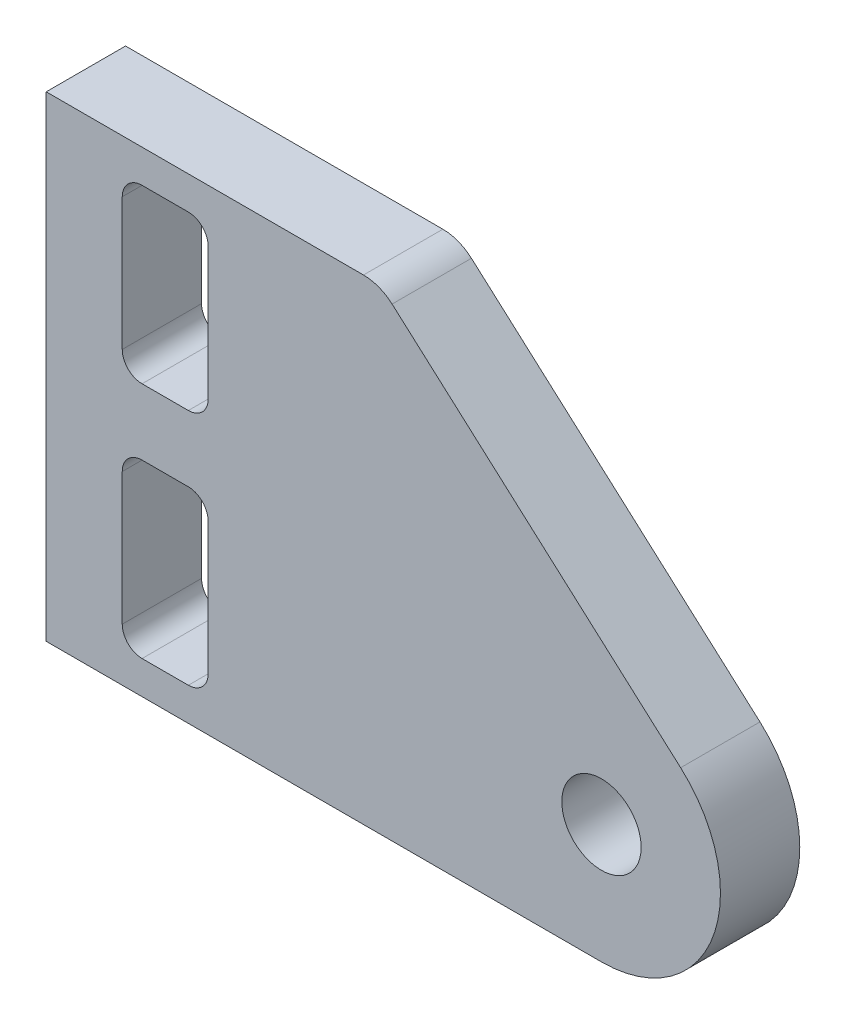
SolidWorks part; units mm, degrees
ref_plane "Alzado" through (0, 0, 0) normal (0, 0, 1) x (1, 0, 0)
ref_plane "Planta" through (0, 0, 0) normal (0, 1, 0) x (1, 0, 0)
ref_plane "Vista lateral" through (0, 0, 0) normal (1, 0, 0) x (0, 0, -1)
sketch "Model" plane through (0, 0, 0) normal (0, 0, 1) x (1, 0, 0)
  line L0 (201.0979, 264.6465) -> (180.0979, 264.6465)
  line L1 (183.7229, 265.8965) -> (185.4729, 265.8965)
  line L2 (186.2229, 266.6465) -> (186.2229, 271.6465)
  line L3 (185.4729, 272.3965) -> (183.7229, 272.3965)
  line L4 (182.9729, 271.6465) -> (182.9729, 266.6465)
  line L5 (192.0979, 282.6465) -> (180.0979, 282.6465)
  line L6 (193.1792, 282.2345) -> (204.0924, 272.5055)
  line L7 (183.7229, 274.896) -> (185.4729, 274.896)
  line L8 (186.2229, 275.646) -> (186.2229, 280.646)
  line L9 (185.4729, 281.396) -> (183.7229, 281.396)
  line L10 (182.9729, 280.646) -> (182.9729, 275.646)
  line L11 (180.0979, 282.6465) -> (180.0979, 264.6465)
  arc A0 (201.0979, 264.6465) -> (204.0924, 272.5055) centre (201.0979, 269.1465) ccw
  circle A1 centre (201.0979, 269.1465) radius 1.5
  arc A2 (182.9729, 266.6465) -> (183.7229, 265.8965) centre (183.7229, 266.6465) ccw
  arc A3 (185.4729, 265.8965) -> (186.2229, 266.6465) centre (185.4729, 266.6465) ccw
  arc A4 (186.2229, 271.6465) -> (185.4729, 272.3965) centre (185.4729, 271.6465) ccw
  arc A5 (183.7229, 272.3965) -> (182.9729, 271.6465) centre (183.7229, 271.6465) ccw
  arc A6 (193.1792, 282.2345) -> (192.0979, 282.6465) centre (192.0979, 281.0215) ccw
  arc A7 (182.9729, 275.646) -> (183.7229, 274.896) centre (183.7229, 275.646) ccw
  arc A8 (185.4729, 274.896) -> (186.2229, 275.646) centre (185.4729, 275.646) ccw
  arc A9 (186.2229, 280.646) -> (185.4729, 281.396) centre (185.4729, 280.646) ccw
  arc A10 (183.7229, 281.396) -> (182.9729, 280.646) centre (183.7229, 280.646) ccw
extrude "Saliente-Extruir1" add sketch "Model" along normal blind 3
